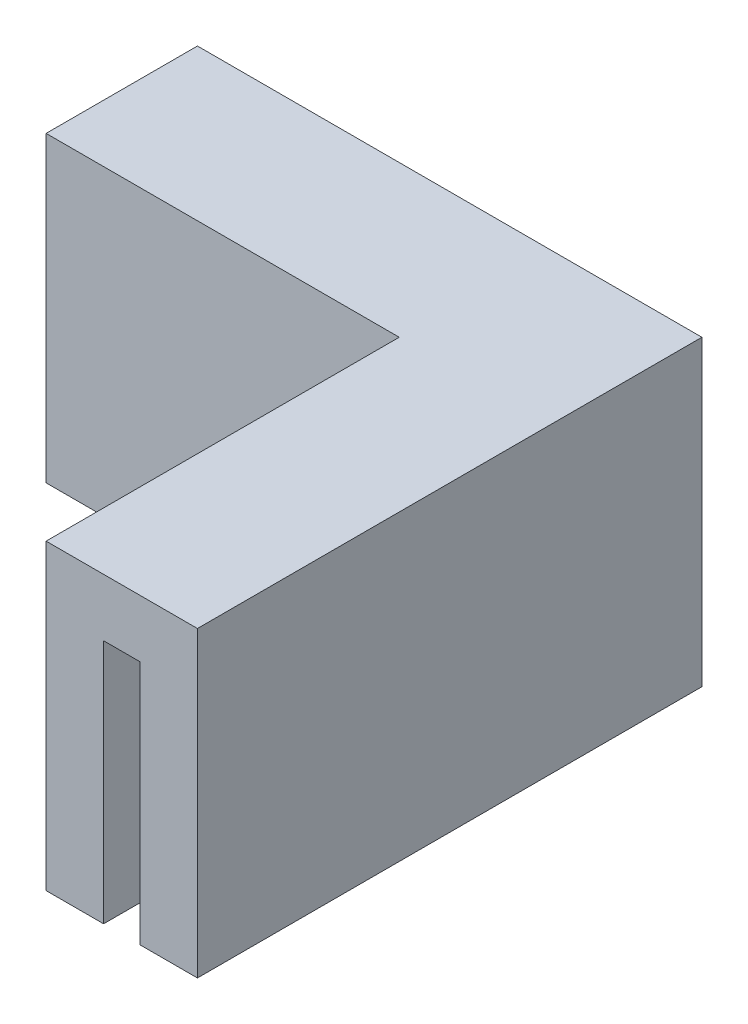
SolidWorks part; units mm, degrees
ref_plane "Plan de face" through (0, 0, 0) normal (0, 0, 1) x (1, 0, 0)
ref_plane "Plan de dessus" through (0, 0, 0) normal (0, 1, 0) x (1, 0, 0)
ref_plane "Plan de droite" through (0, 0, 0) normal (1, 0, 0) x (0, 0, -1)
sketch "Esquisse1" plane through (0, 0, 0) normal (0, 1, 0) x (1, 0, 0)
  line L0 (0, 0) -> (0, -15)
  line L1 (0, 0) -> (50, 0)
  line L2 (50, 0) -> (50, -50)
  line L3 (50, -50) -> (35, -50)
  line L4 (0, -15) -> (35, -15)
  line L5 (35, -15) -> (35, -50)
  dimension "D1" = 15
  dimension "D2" = 50
  dimension "D3" = 50
  dimension "D4" = 15
extrude "Boss.-Extru.1" add sketch "Esquisse1" along normal blind 30
sketch "Esquisse2" plane through (0, 0, 0) normal (0, -1, 0) x (1, 0, 0)
  line L0 (0, 0) -> (0, 15) construction
  line L1 (0, 15) -> (35, 15) construction
  line L2 (35, 50) -> (50, 50) construction
  line L3 (40.7, 50) -> (40.7, 9.3)
  line L4 (40.7, 9.3) -> (0, 9.3)
  line L5 (0, 5.7) -> (44.3, 5.7)
  line L6 (44.3, 5.7) -> (44.3, 50)
  line L7 (0, 5.7) -> (0, 9.3)
  line L9 (44.3, 50) -> (40.7, 50)
  point P0 (0, 5.7)
  point P1 (0, 9.3)
  point P7 (40.7, 50)
  point P8 (44.3, 50)
  dimension "D1" = 5.7
  dimension "D2" = 5.7
  dimension "D3" = 5.7
  dimension "D4" = 5.7
extrude "Enlèv. mat.-Extru.1" cut sketch "Esquisse2" against normal blind 24.3
sketch "Esquisse5" plane through (0, 24.3, 0) normal (0, -1, 0) x (1, 0, 0)
  line L0 (44.3, 5.7) -> (40.6, 5.7)
  line L1 (0, 5.7) -> (44.3, 5.7) construction
  line L2 (40.6, 5.7) -> (40.6, 9.4)
  line L3 (44.3, 5.7) -> (44.3, 9.4)
  line L4 (44.3, 5.7) -> (44.3, 50) construction
  line L5 (44.3, 9.4) -> (40.6, 9.4)
  dimension "D1" = 3.7
  dimension "D2" = 3.7
extrude "Boss.-Extru.5" add sketch "Esquisse5" along normal blind 24.3
